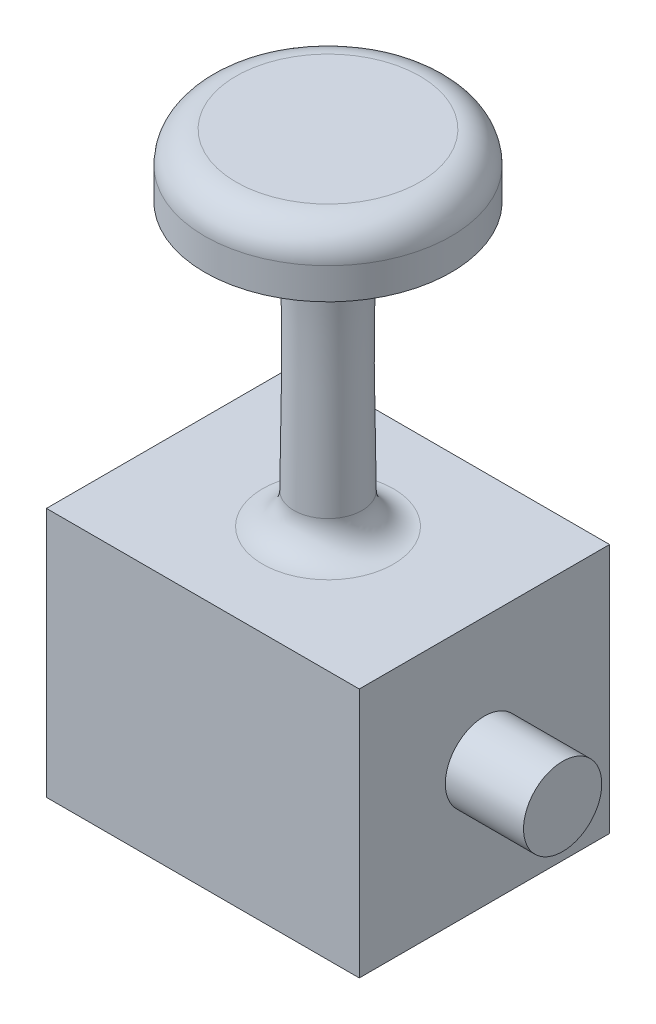
SolidWorks part; units mm, degrees
ref_plane "Front Plane" through (0, 0, 0) normal (0, 0, 1) x (1, 0, 0)
ref_plane "Top Plane" through (0, 0, 0) normal (0, 1, 0) x (1, 0, 0)
ref_plane "Right Plane" through (0, 0, 0) normal (1, 0, 0) x (0, 0, -1)
sketch "Sketch2" plane through (0, 0, 0) normal (1, 0, 0) x (0, 0, -1)
  line L1 (0, 0) -> (20.32, 0)
  line L2 (0, 0) -> (0, 20.32)
  line L3 (0, 20.32) -> (20.32, 20.32)
  line L4 (20.32, 0) -> (20.32, 20.32)
  dimension "D1" = 20.32
  dimension "D2" = 20.32
extrude "central box" add sketch "Sketch2" along normal blind 25.4
ref_point "center for extrusion of nibbles"
sketch "Sketch4" plane through (25.4, 0, 0) normal (1, 0, 0) x (0, 0, -1)
  circle A0 centre (10.16, 10.16) radius 3.175
  dimension "D1" = 6.35
extrude "nibbles" add sketch "Sketch4" along normal blind 6.35 and the other way blind 31.75
ref_point "stick extrusion spot"
ref_plane "stick drawin' plane" through (0, 0, -10.16) normal (0, 0, 1) x (1, 0, 0)
sketch "Sketch6" plane through (0, 0, -10.16) normal (0, 0, 1) x (1, 0, 0)
  line L0 (12.7, 20.32) -> (12.7, 48.26)
  line L1 (12.7, 48.26) -> (22.6999, 48.26)
  line L2 (22.6999, 48.26) -> (22.6999, 43.18)
  line L3 (12.7, 20.32) -> (15.494, 20.32)
  spline S0 degree 3 poles (22.6999, 43.18) (14.0117, 53.9879) (15.3891, 36.9358) (15.494, 20.32) knots 0 0 0 0 1 1 1 1
  dimension "D1" = 2.794
  dimension "D2" = 27.94
  dimension "D3" = 5.08
revolve "stick" add sketch "Sketch6" angle 360 about L0
fillet "yay, rounded" radius 2.54 2 edges at (12.7, 20.32, -12.954) (12.7, 48.26, -20.1599)
